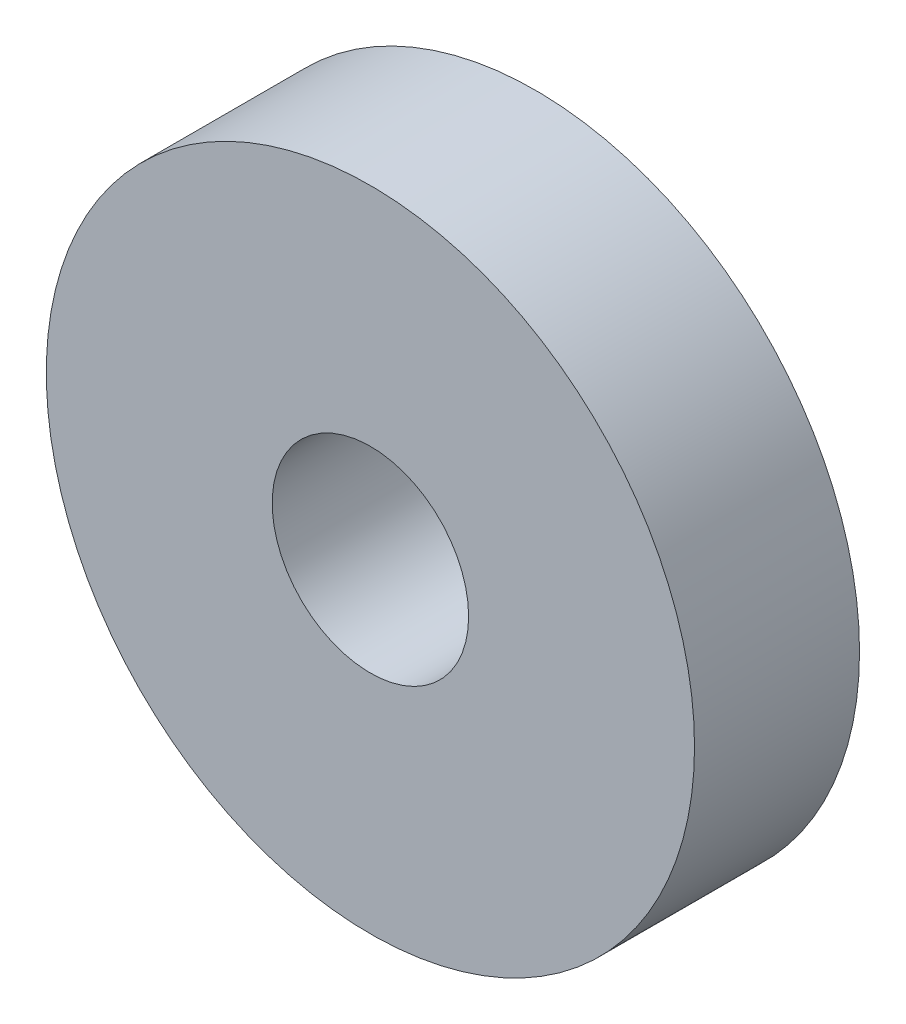
SolidWorks part; units mm, degrees
material "Hardboard"
ref_plane "Front Plane" through (0, 0, 0) normal (0, 0, 1) x (1, 0, 0)
ref_plane "Top Plane" through (0, 0, 0) normal (0, 1, 0) x (1, 0, 0)
ref_plane "Right Plane" through (0, 0, 0) normal (1, 0, 0) x (0, 0, -1)
sketch "Sketch2" plane through (0, 0, 0) normal (0, 0, 1) x (1, 0, 0)
  circle A0 centre (0, 0) radius 2.3813
  circle A1 centre (0, 0) radius 7.8578
  dimension "D1" = 4.7625
extrude "Boss-Extrude1" add sketch "Sketch2" along normal mid plane 4
